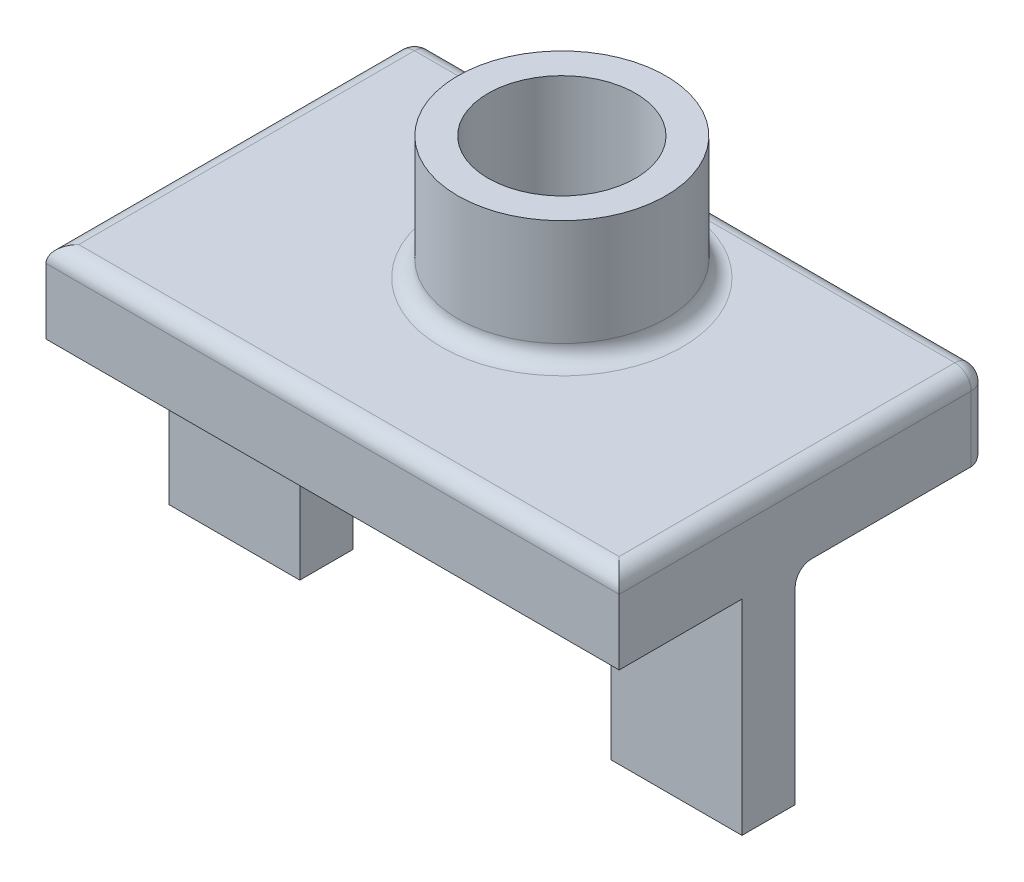
SolidWorks part; units mm, degrees
ref_plane "Front Plane" through (0, 0, 0) normal (0, 0, 1) x (1, 0, 0)
ref_plane "Top Plane" through (0, 0, 0) normal (0, 1, 0) x (1, 0, 0)
ref_plane "Right Plane" through (0, 0, 0) normal (1, 0, 0) x (0, 0, -1)
sketch "Sketch1" plane through (0, 0, 0) normal (0, 1, 0) x (1, 0, 0)
  line L1 (-36.4795, 17.8468) -> (33.5205, 17.8468)
  line L2 (-36.4795, 17.8468) -> (-36.4795, -27.1532)
  line L3 (-36.4795, -27.1532) -> (33.5205, -27.1532)
  line L4 (33.5205, 17.8468) -> (33.5205, -27.1532)
  dimension "D1" = 70
  dimension "D2" = 45
extrude "Boss-Extrude1" add sketch "Sketch1" along normal blind 10
sketch "Sketch2" plane through (0, 0, 0) normal (0, -1, 0) x (1, 0, 0)
  line L0 (33.5205, 27.1532) -> (33.5205, -17.8468) construction
  line L1 (28.5205, 24.1532) -> (17.5205, 24.1532)
  line L2 (28.5205, 21.1532) -> (28.5205, 12.1532)
  line L3 (28.5205, 12.1532) -> (17.5205, 12.1532)
  line L4 (17.5205, 24.1532) -> (17.5205, 12.1532)
  line L5 (33.5205, -17.8468) -> (-36.4795, -17.8468) construction
  line L6 (-1.4795, 27.1532) -> (-1.4795, -17.8468) construction
  line L7 (28.5205, 24.1532) -> (32.5205, 24.1532)
  line L9 (28.5205, 21.1532) -> (32.5205, 21.1532)
  line L10 (32.5205, 24.1532) -> (32.5205, 21.1532)
  line L11 (-36.4795, 27.1532) -> (33.5205, 27.1532) construction
  line L12 (-31.4795, 21.1532) -> (-35.4795, 21.1532)
  line L13 (-35.4795, 24.1532) -> (-35.4795, 21.1532)
  line L14 (-31.4795, 24.1532) -> (-35.4795, 24.1532)
  line L15 (-20.4795, 24.1532) -> (-20.4795, 12.1532)
  line L16 (-31.4795, 12.1532) -> (-20.4795, 12.1532)
  line L17 (-31.4795, 21.1532) -> (-31.4795, 12.1532)
  line L18 (-31.4795, 24.1532) -> (-20.4795, 24.1532)
  dimension "D1" = 12
  dimension "D2" = 11
  dimension "D3" = 5
  dimension "D4" = 30
  dimension "D5" = 4
  dimension "D6" = 3
extrude "Cut-Extrude1" cut sketch "Sketch2" against normal blind 5
fillet "Fillet1" radius 2 7 edges at (-1.4795, 10, 27.1532) (-1.4795, 0, -17.8468) (-36.4795, 5, -17.8468) (-1.4795, 10, -17.8468) (33.5205, 5, -17.8468) (-36.4795, 10, 4.6532) (33.5205, 10, 4.6532)
sketch "Sketch3" plane through (0, 10, 0) normal (0, 1, 0) x (1, 0, 0)
  line L0 (33.5205, -27.1532) -> (33.5205, 15.8468) construction
  line L1 (31.5205, 15.8468) -> (-34.4795, 15.8468) construction
  circle A0 centre (-1.4795, 0.8468) radius 9
  dimension "D1" = 35
  dimension "D2" = 15
extrude "Cut-Extrude3" cut sketch "Sketch3" against normal blind 25
sketch "Sketch5" plane through (0, 10, 0) normal (0, 1, 0) x (1, 0, 0)
  line L0 (-36.4795, -27.1532) -> (-36.4795, 15.8468) construction
  line L2 (31.5205, 15.8468) -> (-34.4795, 15.8468) construction
  circle A0 centre (-1.4795, 0.8468) radius 12.7
  circle A1 centre (-1.4795, 0.8468) radius 9
  dimension "D1" = 35
  dimension "D3" = 15
extrude "Boss-Extrude2" add sketch "Sketch5" along normal blind 15
fillet "Fillet2" radius 2 1 edges at (-1.4795, 10, 11.8532)
sketch "Sketch6" plane through (0, 0, 0) normal (0, -1, 0) x (1, 0, 0)
  line L0 (-36.4795, -15.8468) -> (-36.4795, 27.1532) construction
  line L1 (-36.4795, -15.8468) -> (33.5205, -15.8468) construction
  circle A0 centre (-1.4795, -0.8468) radius 12.7
  circle A1 centre (-1.4795, -0.8468) radius 9
  dimension "D1" = 35
  dimension "D2" = 15
extrude "Boss-Extrude3" add sketch "Sketch6" along normal blind 8 contours A0
fillet "Fillet3" radius 2 1 edges at (-1.4795, 0, 11.8532)
sketch "Sketch7" plane through (0, 0, 0) normal (0, 1, 0) x (1, 0, 0)
  circle A0 centre (-1.4795, 0.8468) radius 9
  circle A1 centre (-1.4795, 0.8468) radius 9 construction
  dimension "D1" = 0
extrude "Cut-Extrude4" cut sketch "Sketch7" against normal blind 5
sketch "Sketch8" plane through (0, 0, 0) normal (0, -1, 0) x (1, 0, 0)
  line L0 (-36.4795, -15.8468) -> (-36.4795, 27.1532) construction
  line L1 (-20.4795, 12.1532) -> (-36.4795, 12.1532)
  line L2 (-20.4795, 12.1532) -> (-20.4795, 5.6532)
  line L3 (-20.4795, 5.6532) -> (-36.4795, 5.6532)
  line L4 (-36.4795, 12.1532) -> (-36.4795, 5.6532)
  line L5 (33.5205, 27.1532) -> (33.5205, -15.8468) construction
  line L6 (17.5205, 12.1532) -> (33.5205, 12.1532)
  line L7 (17.5205, 12.1532) -> (17.5205, 5.6532)
  line L8 (17.5205, 5.6532) -> (33.5205, 5.6532)
  line L9 (33.5205, 12.1532) -> (33.5205, 5.6532)
extrude "Boss-Extrude4" add sketch "Sketch8" along normal blind 25
fillet "Fillet4" radius 2 4 edges at (17.5205, 0, 8.9032) (25.5205, 0, 5.6532) (-20.4795, 0, 8.9032) (-28.4795, 0, 5.6532)
